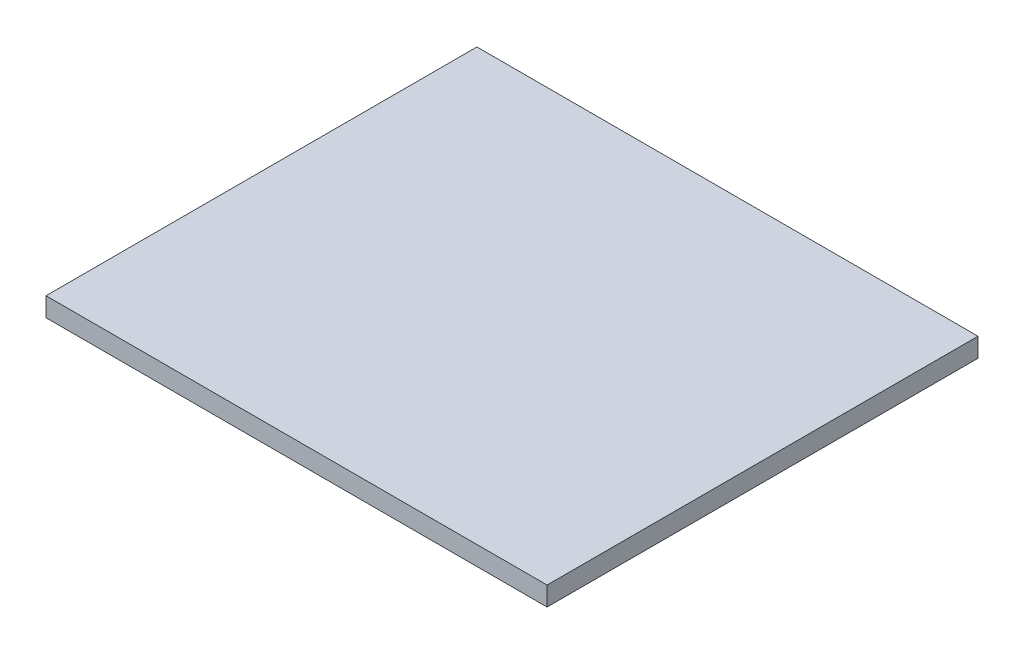
SolidWorks part; units mm, degrees
ref_plane "Front Plane" through (0, 0, 0) normal (0, 0, 1) x (1, 0, 0)
ref_plane "Top Plane" through (0, 0, 0) normal (0, 1, 0) x (1, 0, 0)
ref_plane "Right Plane" through (0, 0, 0) normal (1, 0, 0) x (0, 0, -1)
sketch "Sketch1" plane through (0, 0, 0) normal (0, 1, 0) x (1, 0, 0)
  line L1 (-250, -215) -> (250, -215)
  line L2 (-250, -215) -> (-250, 215)
  line L3 (-250, 215) -> (250, 215)
  line L4 (250, -215) -> (250, 215)
  line L5 (-250, -215) -> (250, 215) construction
  line L6 (-250, 215) -> (250, -215) construction
  point P0 (0, 0)
  dimension "D1" = 500
  dimension "D2" = 430
extrude "Boss-Extrude1" add sketch "Sketch1" along normal blind 19.05
